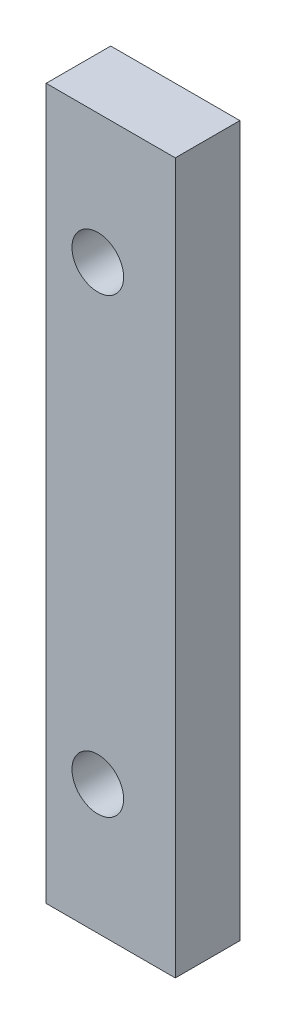
SolidWorks part; units mm, degrees
ref_plane "Front Plane" through (0, 0, 0) normal (0, 0, 1) x (1, 0, 0)
ref_plane "Top Plane" through (0, 0, 0) normal (0, 1, 0) x (1, 0, 0)
ref_plane "Right Plane" through (0, 0, 0) normal (1, 0, 0) x (0, 0, -1)
sketch "Sketch1" plane through (0, 0, 0) normal (0, 0, 1) x (1, 0, 0)
  line L0 (-6, 10) -> (-6, 0) construction
  line L1 (0, 0) -> (-10, 0)
  line L2 (0, 0) -> (0, 55)
  line L3 (0, 55) -> (-10, 55)
  line L4 (-10, 0) -> (-10, 55)
  line L5 (-6, 45) -> (-6, 55) construction
  circle A0 centre (-6, 45) radius 2
  circle A1 centre (-6, 10) radius 2
  dimension "D3" = 4
  dimension "D4" = 4
  dimension "D5" = 4
  dimension "D6" = 4
  dimension "D7" = 35
  dimension "D1" = 55
  dimension "D2" = 10
extrude "Boss-Extrude1" add sketch "Sketch1" along normal blind 5
